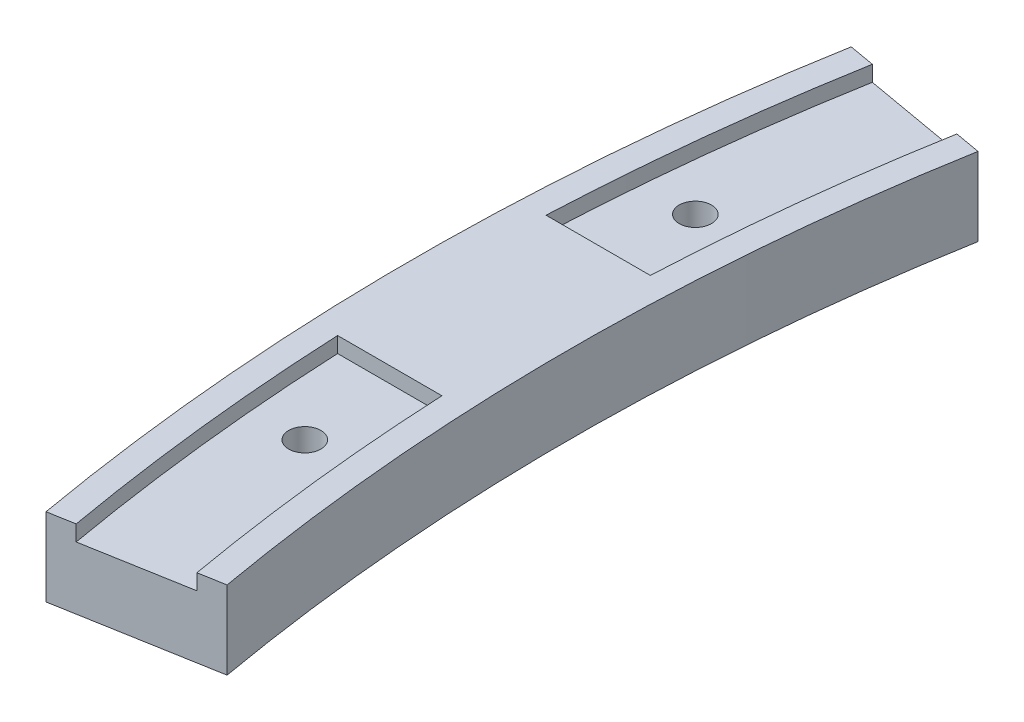
SolidWorks part; units mm, degrees
ref_plane "Front Plane" through (0, 0, 0) normal (0, 0, 1) x (1, 0, 0)
ref_plane "Top Plane" through (0, 0, 0) normal (0, 1, 0) x (1, 0, 0)
ref_plane "Right Plane" through (0, 0, 0) normal (1, 0, 0) x (0, 0, -1)
sketch "Sketch1" plane through (0, 0, 0) normal (0, 1, 0) x (1, 0, 0)
  line L0 (0, 0) -> (-219.1197, -38.6367) construction
  line L1 (0, 0) -> (-219.1197, 38.6367) construction
  line L2 (0, 0) -> (-215, 0) construction
  line L3 (-219.1197, 38.6367) -> (-204.3476, 36.032)
  line L4 (-204.3476, -36.032) -> (-219.1197, -38.6367)
  arc A0 (-216.6577, 38.2026) -> (-216.6577, -38.2026) centre (0, 0) ccw construction
  arc A1 (-206.8096, 36.4661) -> (-206.8096, -36.4661) centre (0, 0) ccw construction
  arc A2 (-211.7337, -37.3344) -> (-211.7337, 37.3344) centre (0, 0) cw construction
  arc A3 (-219.1197, 38.6367) -> (-219.1197, -38.6367) centre (0, 0) ccw
  arc A4 (-204.3476, 36.032) -> (-204.3476, -36.032) centre (0, 0) ccw
  dimension "D1" = 220
  dimension "D2" = 210
  dimension "D3" = 5
  dimension "D5" = 2.5
  dimension "D6" = 2.5
  dimension "D4" = 20
extrude "Boss-Extrude1" add sketch "Sketch1" along normal blind 7.5
sketch "Sketch2" plane through (0, 7.5, 0) normal (0, 1, 0) x (1, 0, 0)
  line L2 (0, 0) -> (-215, 0) construction
  line L3 (0, 0) -> (-219.1197, -38.6367) construction
  line L4 (0, 0) -> (-219.1197, 38.6367) construction
  line L5 (0, 0) -> (-210, 0) construction
  line L6 (0, 0) -> (-219.1197, -38.6367) construction
  line L7 (0, 0) -> (-219.1197, 38.6367) construction
  line L8 (0, 10) -> (-222.2752, 10) construction
  line L9 (0, 10) -> (0, -10) construction
  line L10 (0, -10) -> (-222.2752, -10) construction
  line L11 (-216.6577, 38.2026) -> (-206.8096, 36.4661)
  line L12 (-216.6577, -38.2026) -> (-206.8096, -36.4661)
  line L13 (-219.7726, -10) -> (-209.7618, -10)
  line L14 (-209.7618, 10) -> (-219.7726, 10)
  arc A0 (-216.6577, 38.2026) -> (-216.6577, -38.2026) centre (0, 0) ccw construction
  arc A1 (-206.8096, 36.4661) -> (-206.8096, -36.4661) centre (0, 0) ccw construction
  arc A2 (-216.6577, 38.2026) -> (-216.6577, -38.2026) centre (0, 0) ccw
  arc A3 (-206.8096, 36.4661) -> (-206.8096, -36.4661) centre (0, 0) ccw
  arc A4 (-219.1197, 38.6367) -> (-219.1197, -38.6367) centre (0, 0) ccw construction
  line M2 (-219.1197, -38.6367) -> (-204.3476, -36.032)
  line M4 (-204.3476, 36.032) -> (-219.1197, 38.6367)
  dimension "D1" = 20
extrude "Cut-Extrude1" cut sketch "Sketch2" against normal blind 1.5 contours A3 A2 L14 M4 | A3 L13 A2 M2
ref_plane "Plane1" through (-215, 0, 0) normal (1, 0, 0) x (0, 0, -1)
sketch "Sketch6" plane through (0, 0, 0) normal (0, -1, 0) x (1, 0, 0)
  line L0 (0, 0) -> (-214.1819, 18.7385) construction
  line L1 (0, 0) -> (-215, 0) construction
  line L2 (0, 0) -> (-215, 0) construction
  line L3 (0, 0) -> (-214.1819, -18.7385) construction
  arc A0 (-211.7337, 37.3344) -> (-211.7337, -37.3344) centre (0, 0) ccw construction
  dimension "D1" = 5
hole_wizard "Ø3.1 (3.1) Diameter Hole1" positions "Sketch7" profile "Sketch8" hole size "Ø3.1" standard "ISO" end condition through all
sketch "Sketch7" plane through (0, 0, 0) normal (0, -1, 0) x (-1, 0, 0)
  point P0 (214.1819, -18.7385)
  point P3 (214.1819, 18.7385)
sketch "Sketch8" plane through (-214.1819, 0, 18.7385) normal (1, 0, 0) x (0, 0, -1)
  line L0 (0, 0) -> (0, 7.5)
  line L1 (0, 7.5) -> (1.55, 7.5)
  line L2 (1.55, 7.5) -> (1.55, 0)
  line L5 (1.55, 0) -> (0, 0)
  line L11 (0, -6.35) -> (0, 107.95) construction
  dimension "Thru Hole Dia." = 3.1
  dimension "Thru Hole Depth" = 7.5
